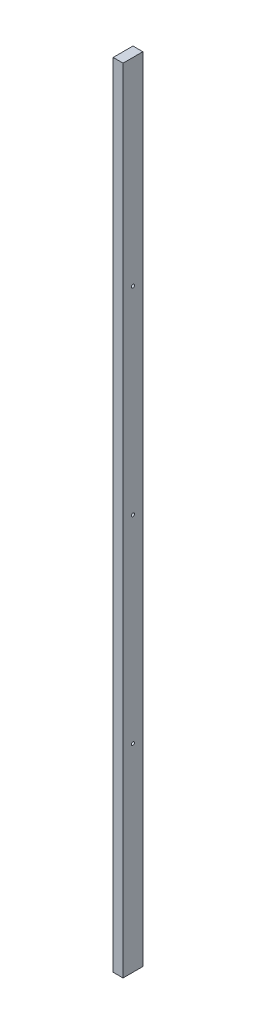
SolidWorks part; units mm, degrees
ref_plane "Спереди" through (0, 0, 0) normal (0, 0, 1) x (1, 0, 0)
ref_plane "Сверху" through (0, 0, 0) normal (0, 1, 0) x (1, 0, 0)
ref_plane "Справа" through (0, 0, 0) normal (1, 0, 0) x (0, 0, -1)
other "Configuration Table"
sketch "Эскиз1" plane through (0, 0, 0) normal (0, 1, 0) x (1, 0, 0)
  line L1 (12.5, 25) -> (-12.5, 25)
  line L2 (12.5, 25) -> (12.5, -25)
  line L3 (12.5, -25) -> (-12.5, -25)
  line L4 (-12.5, 25) -> (-12.5, -25)
  line L5 (12.5, 25) -> (-12.5, -25) construction
  line L6 (12.5, -25) -> (-12.5, 25) construction
  point P0 (0, 0)
extrude "Бобышка-Вытянуть1" add sketch "Эскиз1" along normal blind 2000
sketch "Эскиз2" plane through (12.5, 0, 0) normal (1, 0, 0) x (0, 0, -1)
  line L0 (0, 2000) -> (0, 0) construction
  line L1 (-25, 2000) -> (25, 2000) construction
  line L2 (0, 0) -> (0, 1000) construction
  line L3 (0, 1000) -> (0, 0) construction
  line L4 (0, 0) -> (0, 1000) construction
  line L5 (0, 1000) -> (0, 2000) construction
  line L6 (0, 1000) -> (0, 0) construction
  circle A0 centre (0, 1500) radius 4
  circle A1 centre (0, 500) radius 4
extrude "Вырез-Вытянуть1" cut sketch "Эскиз2" against normal blind 2214.159
sketch "Эскиз3" plane through (12.5, 0, 0) normal (1, 0, 0) x (0, 0, -1)
  line L0 (0, 2000) -> (0, 0) construction
  line L1 (-25, 2000) -> (25, 2000) construction
  circle A0 centre (0, 1000) radius 4
extrude "Вырез-Вытянуть2" cut sketch "Эскиз3" against normal blind 50
